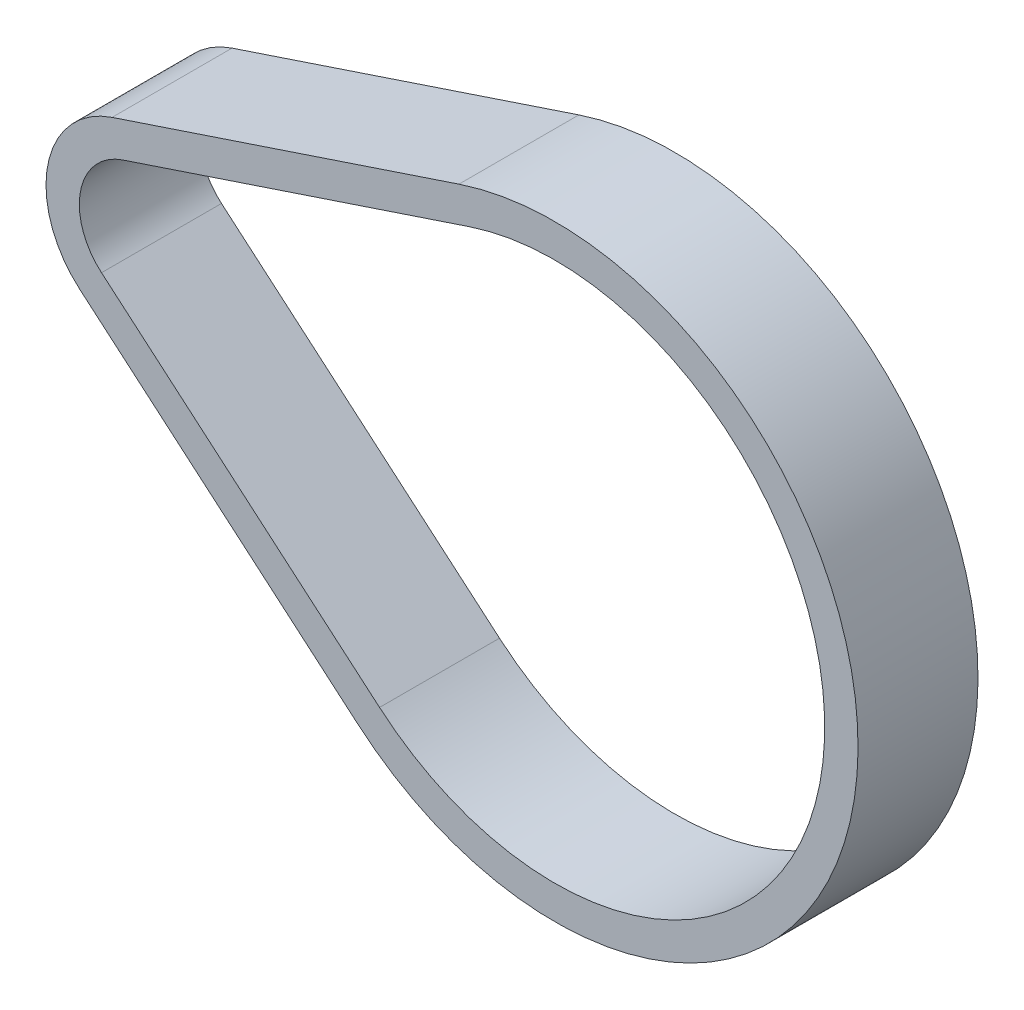
SolidWorks part; units mm, degrees
material "Beryllium"
ref_plane "Front Plane" through (0, 0, 0) normal (0, 0, 1) x (1, 0, 0)
ref_plane "Top Plane" through (0, 0, 0) normal (0, 1, 0) x (1, 0, 0)
ref_plane "Right Plane" through (0, 0, 0) normal (1, 0, 0) x (0, 0, -1)
sketch "Sketch1" plane through (0, 0, 0) normal (0, 0, 1) x (1, 0, 0)
  line L1 (102.4117, 144.7688) -> (206.5134, 179.4636)
  line L2 (94.4125, 103.7509) -> (177.8497, 32.4828)
  arc A0 (102.4117, 144.7688) -> (94.4125, 103.7509) centre (110, 122) ccw
  arc A1 (177.8497, 32.4828) -> (206.5134, 179.4636) centre (233.7049, 97.8755) ccw
  circle A2 centre (110, 122) radius 16 construction
  arc A3 (214.4372, 179.6358) -> (178.671, 161.3362) centre (233.7049, 97.8755) ccw construction
  point P2 (72.5955, 44.4755)
  dimension "D1" = 24
  dimension "D2" = 86
extrude "Extrude-Thin1" add sketch "Sketch1" along normal blind 28 and the other way blind 8 thin thin type mid plane wall 10
